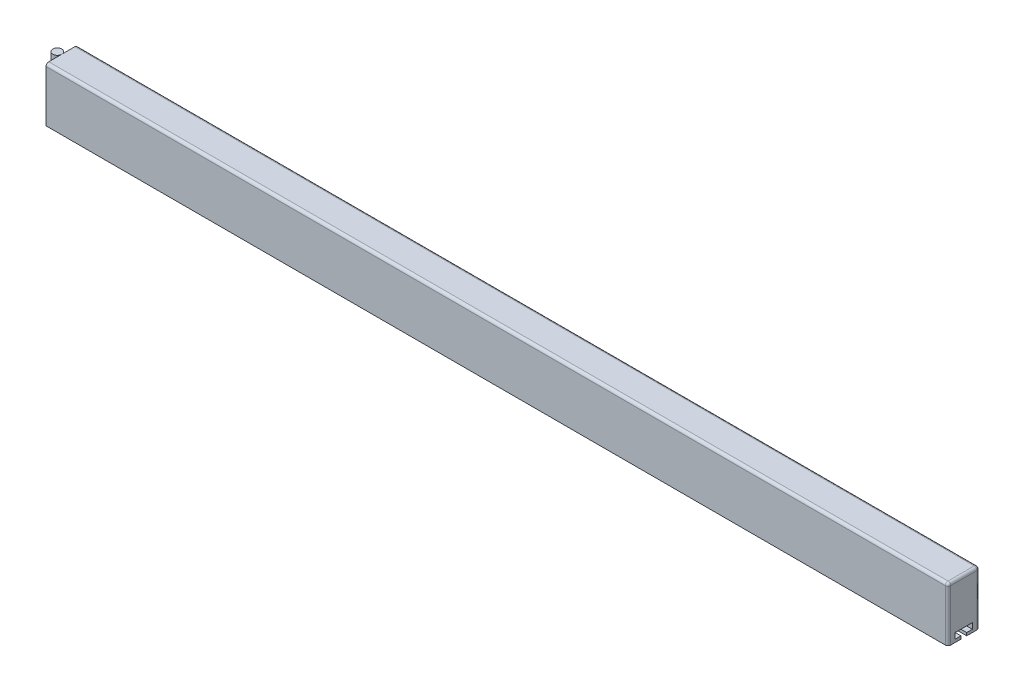
SolidWorks part; units mm, degrees
ref_plane "Alzado" through (0, 0, 0) normal (0, 0, 1) x (1, 0, 0)
ref_plane "Planta" through (0, 0, 0) normal (0, 1, 0) x (1, 0, 0)
ref_plane "Vista lateral" through (0, 0, 0) normal (1, 0, 0) x (0, 0, -1)
sketch "Croquis1" plane through (0, 0, 0) normal (0, 0, 1) x (1, 0, 0)
  line L1 (-1000, -60) -> (1000, -60)
  line L2 (-1000, -60) -> (-1000, 60)
  line L3 (-1000, 60) -> (1000, 60)
  line L4 (1000, -60) -> (1000, 60)
  line L5 (-1000, -60) -> (1000, 60) construction
  line L6 (-1000, 60) -> (1000, -60) construction
  point P0 (0, 0)
  dimension "D1" = 2000
  dimension "D2" = 120
extrude "Saliente-Extruir1" add sketch "Croquis1" along normal blind 70
sketch "Croquis2" plane through (0, 60, 0) normal (0, 1, 0) x (1, 0, 0)
  line L0 (-1000, -35) -> (-1020, -35) construction
  line L1 (-1000, -70) -> (-1000, 0) construction
  circle A0 centre (-1010, -35) radius 10
  dimension "D1" = 20
extrude "Saliente-Extruir2" add sketch "Croquis2" against normal up to surface (120 mm away) separate body up to face at (0, -60, 35)
sketch "Croquis3" plane through (1000, 0, 0) normal (1, 0, 0) x (0, 0, -1)
  line L0 (-35, -60) -> (-35, 60) construction
  line L1 (-70, -60) -> (0, -60) construction
  line L2 (-70, 60) -> (0, 60) construction
  line L3 (-41.35, -60) -> (-41.35, -53.65)
  line L4 (-41.35, -53.65) -> (-54.05, -53.65)
  line L5 (-54.05, -53.65) -> (-54.05, -40.95)
  line L6 (-54.05, -40.95) -> (-15.95, -40.95)
  line L7 (-41.35, -60) -> (-28.65, -60)
  line L8 (-15.95, -53.65) -> (-15.95, -40.95)
  line L9 (-28.65, -53.65) -> (-15.95, -53.65)
  line L10 (-28.65, -60) -> (-28.65, -53.65)
  point P13 (-35, -40.95)
  dimension "D1" = 6.35
  dimension "D2" = 6.35
  dimension "D3" = 12.7
  dimension "D4" = 12.7
extrude "Cortar-Extruir1" cut sketch "Croquis3" against normal up to surface (2000 mm away) up to face at (-1000, 0, 35)
fillet "Redondeo1" radius 6 2 edges at (0, 60, 0) (0, 60, 70)
fillet "Redondeo2" radius 6 5 edges at (1000, -3, 0) (1000, 58.2426, 1.7574) (1000, 60, 35) (1000, 58.2426, 68.2426) (1000, -3, 70)
